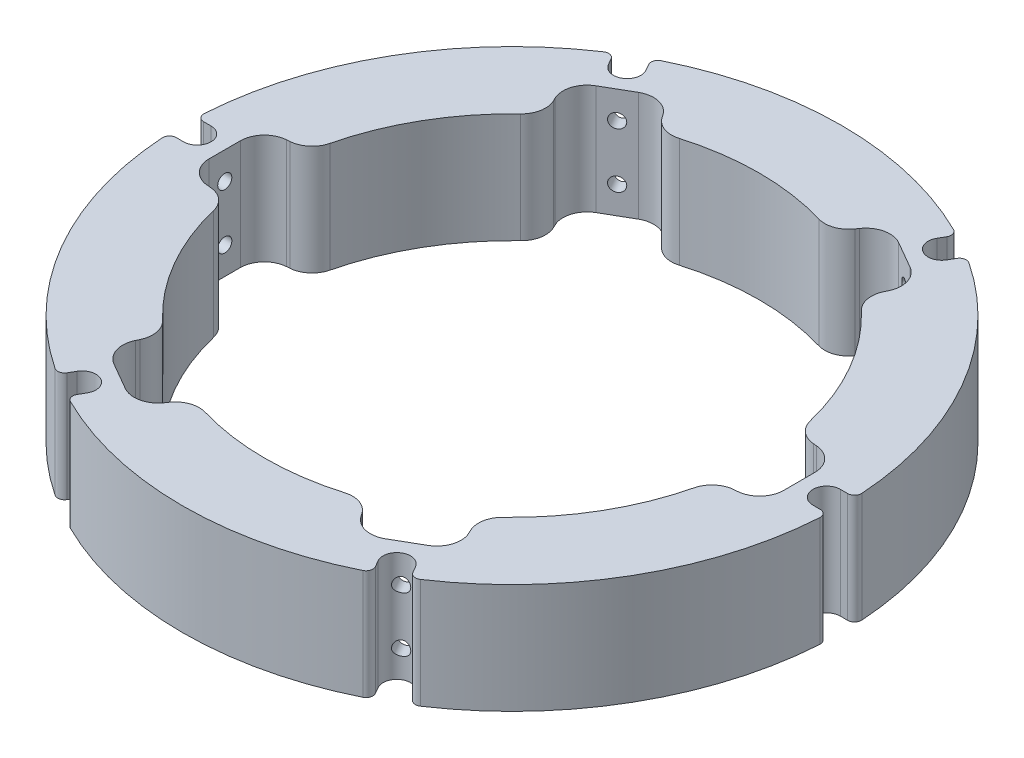
SolidWorks part; units mm, degrees
material "6061-T6 (SS)"
ref_plane "Front Plane" through (0, 0, 0) normal (0, 0, 1) x (1, 0, 0)
ref_plane "Top Plane" through (0, 0, 0) normal (0, 1, 0) x (1, 0, 0)
ref_plane "Right Plane" through (0, 0, 0) normal (1, 0, 0) x (0, 0, -1)
sketch "Sketch1" plane through (0, 0, 0) normal (0, 1, 0) x (1, 0, 0)
  circle A0 centre (0, 0) radius 76.2
  circle A1 centre (0, 0) radius 57.15
  dimension "D1" = 152.4
  dimension "D2" = 19.05
extrude "Boss-Extrude1" add sketch "Sketch1" against normal blind 12.7
sketch "Sketch3" plane through (0, -12.7, 0) normal (0, -1, 0) x (-1, 0, 0)
  line L0 (-76.1338, 3.175) -> (-72.771, 3.175)
  line L1 (-76.1338, -3.175) -> (-72.771, -3.175)
  circle A0 centre (0, 0) radius 76.2 construction
  arc A1 (-72.771, 3.175) -> (-72.771, -3.175) centre (-72.771, 0) cw
  arc A2 (-76.1338, -3.175) -> (-76.1338, 3.175) centre (0, 0) cw
  point P9 (-69.596, 0)
  point P13 (-76.2, 0)
  dimension "D1" = 6.35
  dimension "D2" = 6.604
extrude "Cut-Extrude1" cut sketch "Sketch3" against normal blind 12.7
sketch "Sketch4" plane through (0, -12.7, 0) normal (0, -1, 0) x (-1, 0, 0)
  line L0 (-66.421, 8.7312) -> (-66.421, -8.7312)
  line L1 (-66.421, -8.7312) -> (-56.3507, -9.525)
  line L2 (-56.3507, -9.525) -> (-56.3507, 9.525)
  line L3 (-56.3507, 9.525) -> (-66.421, 8.7312)
  line L4 (-66.421, 0) -> (0, 0) construction
  circle A0 centre (0, 0) radius 57.15 construction
  dimension "D1" = 3.175
  dimension "D2" = 19.05
  dimension "D3" = 17.4625
extrude "Cut-Extrude2" cut sketch "Sketch4" against normal through all
hole_wizard "#30 (0.1285) Diameter Hole1" positions "Sketch5" profile "Sketch6" hole size "#30" standard "ANSI Inch"
sketch "Sketch5" plane through (66.421, 0, 0) normal (-1, 0, 0) x (0, 0, 1)
  line L0 (-8.7312, -12.7) -> (8.7312, -12.7) construction
  point P0 (0, -6.35)
  dimension "D1" = 6.35
sketch "Sketch6" plane through (66.421, -6.35, 0) normal (0, 1, 0) x (0, 0, 1)
  line L0 (0, 0) -> (0, 9.7128)
  line L1 (0, 9.7128) -> (1.6319, 9.7128)
  line L2 (1.6319, 9.7128) -> (1.6319, 0)
  line L5 (1.6319, 0) -> (0, 0)
  line L11 (0, -6.35) -> (0, 107.95) construction
  dimension "Thru Hole Dia." = 3.2639
  dimension "Thru Hole Depth" = 9.7128
fillet "Fillet1" radius 1.5875 2 edges at (76.1338, -6.35, 3.175) (76.1338, -6.35, -3.175)
fillet "Fillet2" radius 5.5562 4 edges at (66.421, -6.35, 8.7312) (66.421, -6.35, -8.7312) (56.3507, -6.35, 9.525) (56.3507, -6.35, -9.525)
pattern_circular "CirPattern1" count 6 over 360 about axis through (0, 0, 0) along (0, 1, 0) of "Cut-Extrude1", "Cut-Extrude2", "Fillet2", "Fillet1", "#30 (0.1285) Diameter Hole1"
mirror "Mirror3" about plane through (0, 0, 0) normal (0, 1, 0) of bodies 103
